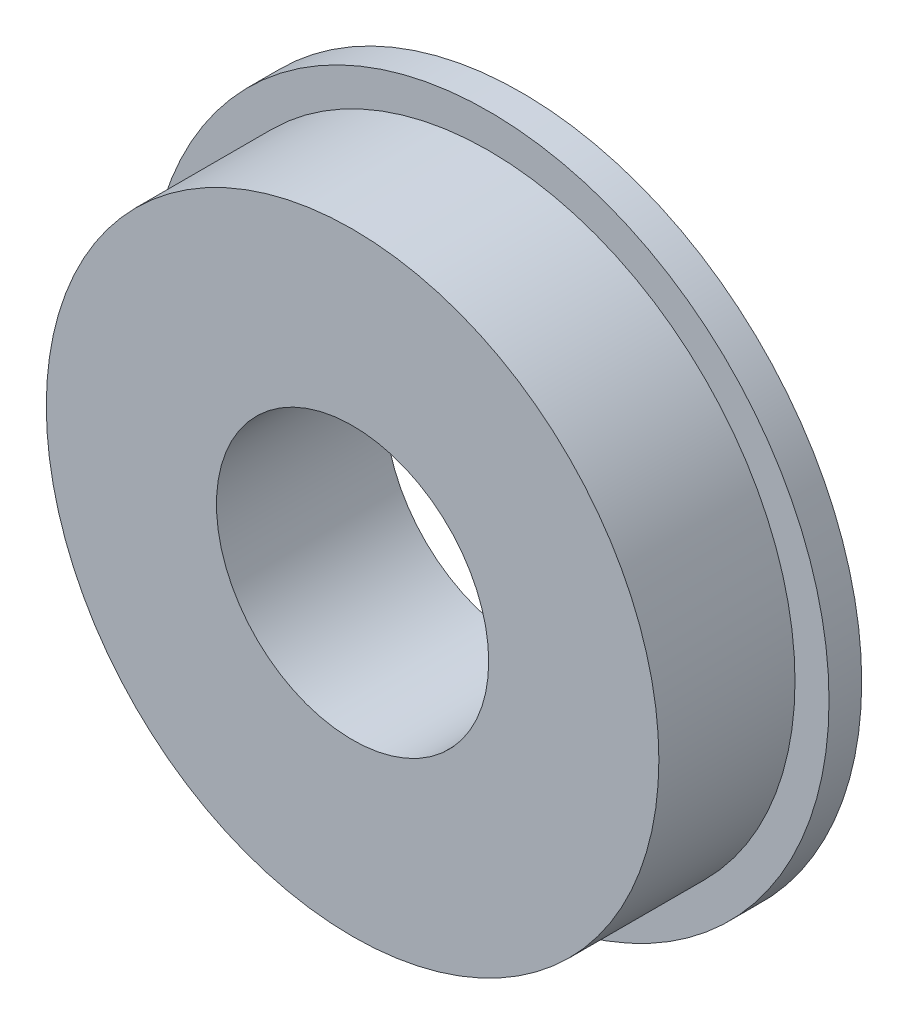
SolidWorks part; units mm, degrees
ref_plane "Front Plane" through (0, 0, 0) normal (0, 0, 1) x (1, 0, 0)
ref_plane "Top Plane" through (0, 0, 0) normal (0, 1, 0) x (1, 0, 0)
ref_plane "Right Plane" through (0, 0, 0) normal (1, 0, 0) x (0, 0, -1)
sketch "Sketch3" plane through (0, 0, 0) normal (1, 0, 0) x (0, 0, -1)
  line L0 (0, 0.25) -> (0, 0.5625)
  line L1 (0, 0.5625) -> (0.25, 0.5625)
  line L2 (0.25, 0.5625) -> (0.25, 0.625)
  line L3 (0.25, 0.625) -> (0.31, 0.625)
  line L4 (0.31, 0.625) -> (0.31, 0.25)
  line L5 (0.31, 0.25) -> (0, 0.25)
  line L6 (0, 0.25) -> (0, 0) construction
  line L7 (0, 0) -> (0, 1.1578) construction
  line L8 (0, 0.5625) -> (0, 0) construction
  line L9 (0, 0.5625) -> (0, 0) construction
  line L10 (-1000, 0) -> (49000, 0) construction
  dimension "D1" = 0.25
  dimension "D2" = 0.3125
  dimension "D3" = 0.375
  dimension "D4" = 0.31
  dimension "D5" = 0.25
revolve "Revolve1" add sketch "Sketch3" angle 360 about L10
